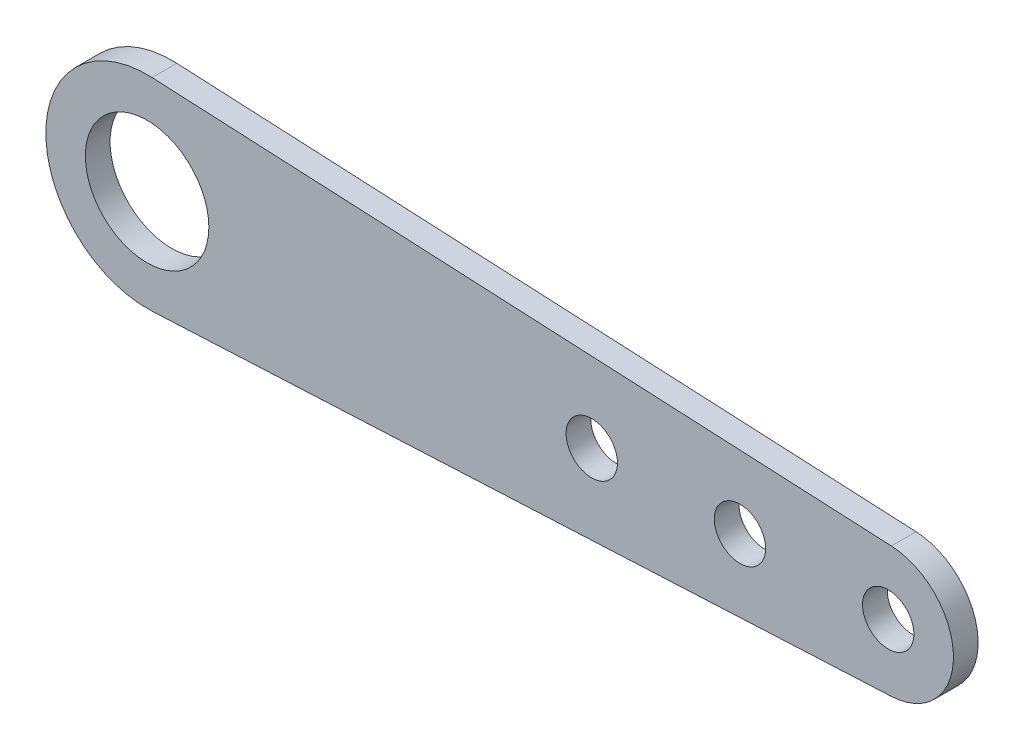
SolidWorks part; units mm, degrees
material "AISI 4130 Steel, annealed at 865C"
ref_plane "Front Plane" through (0, 0, 0) normal (0, 0, 1) x (1, 0, 0)
ref_plane "Top Plane" through (0, 0, 0) normal (0, 1, 0) x (1, 0, 0)
ref_plane "Right Plane" through (0, 0, 0) normal (1, 0, 0) x (0, 0, -1)
sketch "Sketch1" plane through (0, 0, 0) normal (0, 0, 1) x (1, 0, 0)
  line L0 (0, 0) -> (57.15, 0) construction
  line L1 (57.15, 0) -> (76.2, 0) construction
  line L2 (0.6335, 13.0021) -> (95.6579, 8.3721)
  line L3 (0.6335, -13.0021) -> (95.6579, -8.3721)
  arc A0 (0.6335, 13.0021) -> (0.6335, -13.0021) centre (0, 0) ccw
  circle A1 centre (0, 0) radius 7.9375
  circle A2 centre (57.15, 0) radius 3.302
  circle A3 centre (76.2, 0) radius 3.302
  circle A4 centre (95.25, 0) radius 3.302
  arc A5 (95.6579, -8.3721) -> (95.6579, 8.3721) centre (95.25, 0) ccw
  dimension "D1" = 15.875
  dimension "D2" = 5.08
  dimension "D7" = 5.08
  dimension "D3" = 76.2
  dimension "D4" = 19.05
  dimension "D5" = 3
extrude "Extrude - Body" add sketch "Sketch1" along normal blind 3.175
equation "\"Torsion bar hole OD\"= 0.625in"
equation "\"DL Hole ID\"= 0.25"
equation "\"Dist. to middle DL hole\"= 3.0in"
equation "\"Dist. b/w DL holes\"= 0.75in"
equation "\"D1@Sketch1\"=\"Torsion bar hole OD\""
equation "\"D3@Sketch1\"=\"Dist. to middle DL hole\""
equation "\"D4@Sketch1\"=\"Dist. b/w DL holes\""
